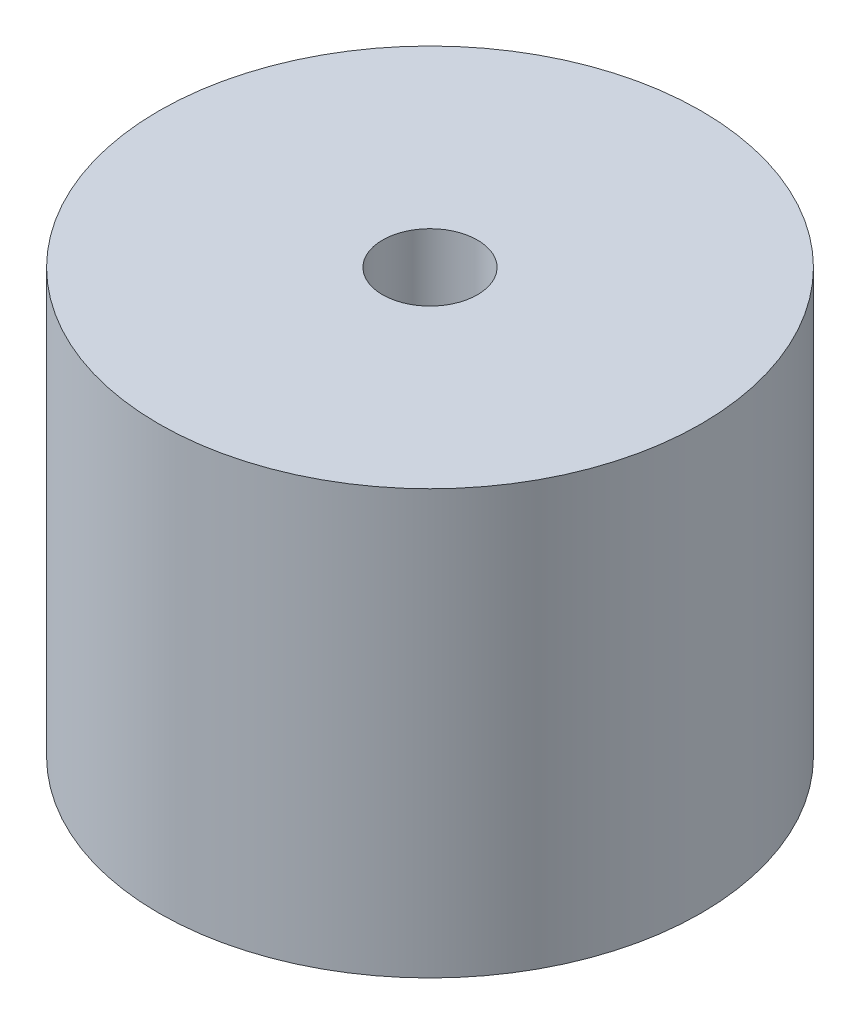
SolidWorks part; units mm, degrees
material "ABS"
ref_plane "Front Plane" through (0, 0, 0) normal (0, 0, 1) x (1, 0, 0)
ref_plane "Top Plane" through (0, 0, 0) normal (0, 1, 0) x (1, 0, 0)
ref_plane "Right Plane" through (0, 0, 0) normal (1, 0, 0) x (0, 0, -1)
sketch "Sketch1" plane through (0, 0, 0) normal (0, 1, 0) x (1, 0, 0)
  circle A0 centre (0, 0) radius 16
  circle A1 centre (0, 0) radius 2.8
  dimension "D1" = 5.6
  dimension "D2" = 32
extrude "Boss-Extrude1" add sketch "Sketch1" against normal blind 25 contours A0 A1
